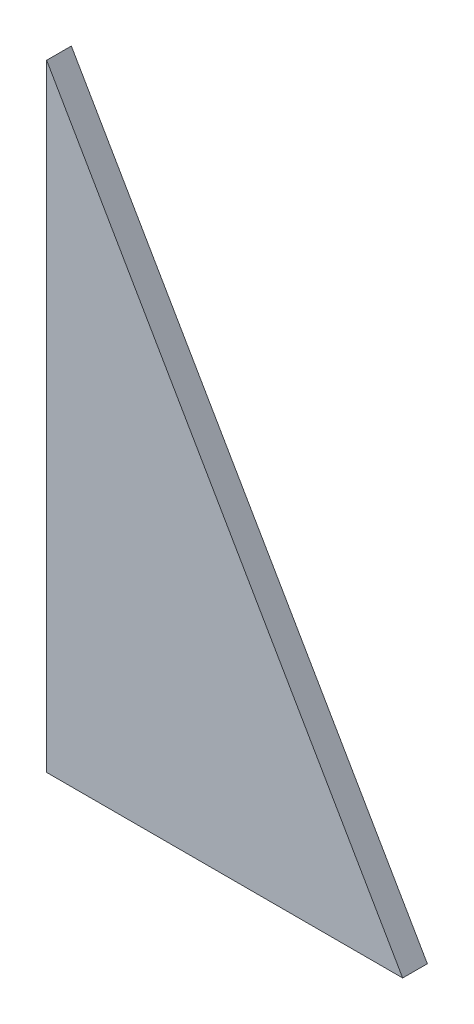
SolidWorks part; units mm, degrees
ref_plane "Front Plane" through (0, 0, 0) normal (0, 0, 1) x (1, 0, 0)
ref_plane "Top Plane" through (0, 0, 0) normal (0, 1, 0) x (1, 0, 0)
ref_plane "Right Plane" through (0, 0, 0) normal (1, 0, 0) x (0, 0, -1)
sketch "Sketch1" plane through (0, 0, 0) normal (0, 0, 1) x (1, 0, 0)
  line L0 (0, 63.5) -> (36.6522, 0)
  line L1 (0, 0) -> (36.6522, 0)
  line L2 (0, 0) -> (0, 63.5)
extrude "Extrude1" add sketch "Sketch1" along normal blind 2.54
sketch "Sketch2" plane through (0, 0, 0) normal (-1, 0, 0) x (0, 0, 1)
  line L0 (0, 31.75) -> (2.54, 31.75) construction
  line L1 (0, 63.5) -> (0, 0) construction
  line L2 (2.54, 63.5) -> (2.54, 0) construction
sketch "Sketch4" plane through (0, 0, 0) normal (0, 0, -1) x (-1, 0, 0)
  line L0 (0, 31.75) -> (0, 35.306)
  line L1 (0, 63.5) -> (0, 0) construction
  line L2 (0, 31.75) -> (0, 28.194)
  line L3 (0, 35.306) -> (-10.668, 35.306)
  line L4 (0, 28.194) -> (-10.668, 28.194)
  line L5 (-10.668, 35.306) -> (-10.668, 28.194)
  point P7 (0, 0)
extrude "Extrude3" cut sketch "Sketch4" against normal blind 2.032
sketch "Sketch3" plane through (0, 0, 0) normal (0, 0, -1) x (-1, 0, 0)
  line L0 (0, 31.75) -> (-2.54, 31.75) construction
  line L1 (-2.54, 31.75) -> (-2.54, 20.955)
  line L2 (0, 28.194) -> (0, 35.306) construction
  line L3 (-2.54, 42.545) -> (-2.54, 31.75)
  line L4 (-2.54, 42.545) -> (-6.8542, 42.545)
  line L5 (-2.54, 20.955) -> (-19.3159, 20.955)
  line L6 (-6.8542, 42.545) -> (-19.3159, 20.955)
  line L7 (-36.6522, 0) -> (0, 63.5) construction
extrude "Extrude2" cut sketch "Sketch3" against normal blind 0.9144
fillet "Fillet1" radius 1.5875 6 edges at (2.54, 20.955, 0.4572) (10.668, 35.306, 1.4732) (10.668, 28.194, 1.4732) (19.3159, 20.955, 0.4572) (6.8542, 42.545, 0.4572) (2.54, 42.545, 0.4572)
